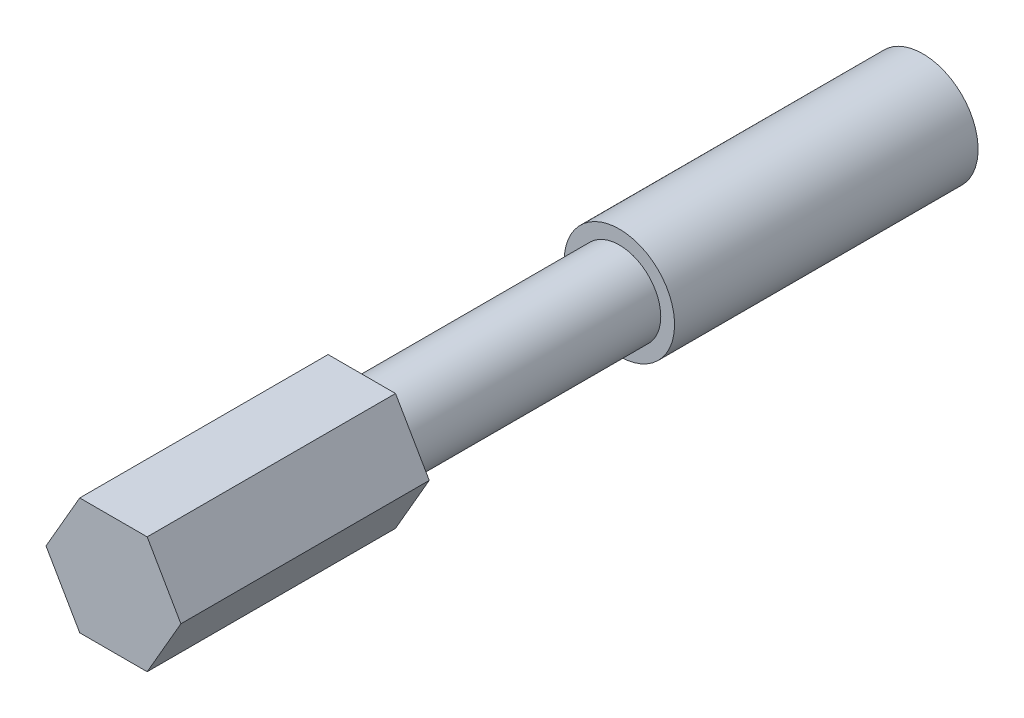
SolidWorks part; units mm, degrees
ref_plane "Front Plane" through (0, 0, 0) normal (0, 0, 1) x (1, 0, 0)
ref_plane "Top Plane" through (0, 0, 0) normal (0, 1, 0) x (1, 0, 0)
ref_plane "Right Plane" through (0, 0, 0) normal (1, 0, 0) x (0, 0, -1)
sketch "Sketch1" plane through (0, 0, 0) normal (0, 0, 1) x (1, 0, 0)
  line L1 (3.6662, -6.35) -> (7.3323, 0)
  line L2 (7.3323, 0) -> (3.6662, 6.35)
  line L3 (3.6662, 6.35) -> (-3.6662, 6.35)
  line L4 (-3.6662, 6.35) -> (-7.3323, 0)
  line L5 (-7.3323, 0) -> (-3.6662, -6.35)
  line L6 (-3.6662, -6.35) -> (3.6662, -6.35)
  circle A0 centre (0, 0) radius 6.35 construction
  dimension "D1" = 12.7
extrude "Boss-Extrude1" add sketch "Sketch1" along normal blind 27
sketch "Sketch2" plane through (0, 0, 0) normal (0, 0, -1) x (-1, 0, 0)
  circle A0 centre (0, 0) radius 4.5
  dimension "D1" = 9
extrude "Boss-Extrude2" add sketch "Sketch2" along normal blind 61
sketch "Sketch3" plane through (0, 0, -61) normal (0, 0, -1) x (-1, 0, 0)
  line L0 (-5, 3) -> (-2.6458, 3) construction
  line L1 (-2.6458, 3) -> (2.6458, 3)
  line L2 (-5, 3) -> (-5, -3) construction
  line L3 (-2.6458, -3) -> (2.6458, -3)
  line L4 (5, 3) -> (5, -3) construction
  line L5 (-5, 3) -> (5, -3) construction
  line L6 (-5, -3) -> (5, 3) construction
  line L7 (-5, -3) -> (-2.6458, -3) construction
  line L8 (2.6458, -3) -> (5, -3) construction
  line L9 (2.6458, 3) -> (5, 3) construction
  arc A0 (-2.6458, 3) -> (-2.6458, -3) centre (0, 0) ccw
  arc A1 (2.6458, 3) -> (-2.6458, 3) centre (0, 0) ccw construction
  arc A2 (-2.6458, -3) -> (2.6458, -3) centre (0, 0) ccw construction
  arc A3 (2.6458, -3) -> (2.6458, 3) centre (0, 0) ccw
  point P0 (0, 0)
  dimension "D1" = 8
  dimension "D2" = 6
  dimension "D3" = 10
extrude "Cut-Extrude1" cut sketch "Sketch3" against normal blind 14
sketch "Sketch4" plane through (0, 0, -61) normal (0, 0, -1) x (-1, 0, 0)
  line L0 (-2.6458, -3) -> (2.6458, -3) construction
  line L1 (2.6458, 3) -> (-2.6458, 3) construction
  line L2 (-2.6458, -3) -> (2.6458, -3)
  line L3 (2.6458, 3) -> (-2.6458, 3)
  arc A0 (-2.6458, 3) -> (-2.6458, -3) centre (0, 0) ccw construction
  circle A1 centre (0, 0) radius 4.5
  circle A2 centre (0, 0) radius 4.5 construction
  arc A3 (2.6458, -3) -> (2.6458, 3) centre (0, 0) ccw construction
  arc A4 (-2.6458, 3) -> (-2.6458, -3) centre (0, 0) ccw
  arc A5 (2.6458, -3) -> (2.6458, 3) centre (0, 0) ccw
  circle A6 centre (0, 0) radius 6
  dimension "D2" = 12
  dimension "D1" = 0
extrude "Boss-Extrude3" add sketch "Sketch4" against normal blind 33
